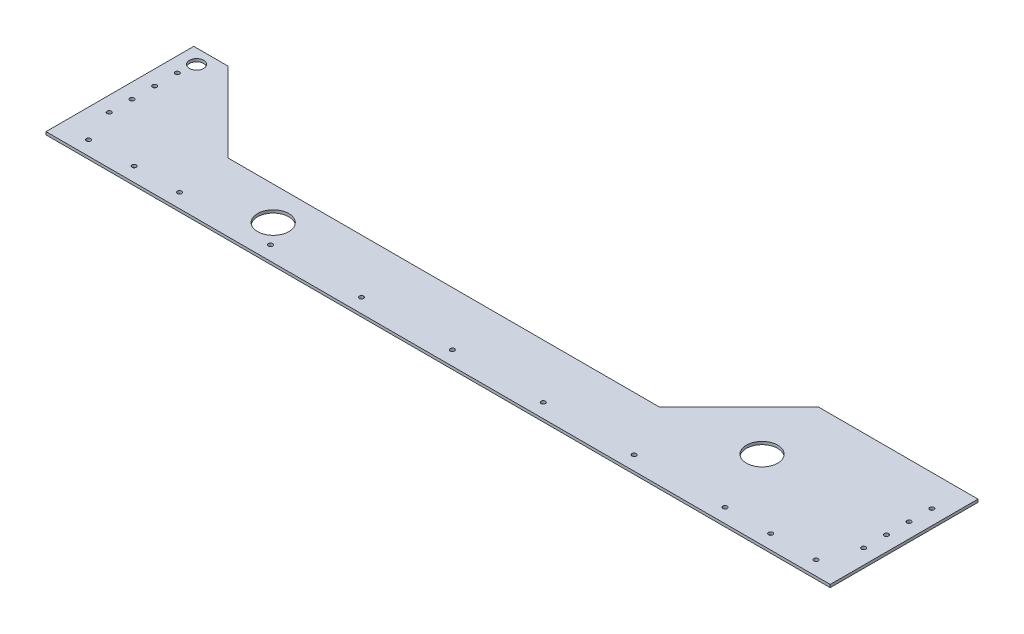
SolidWorks part; units mm, degrees
material "5052-H32"
ref_plane "Front" through (0, 0, 0) normal (0, 0, 1) x (1, 0, 0)
ref_plane "Top" through (0, 0, 0) normal (0, 1, 0) x (1, 0, 0)
ref_plane "Right" through (0, 0, 0) normal (1, 0, 0) x (0, 0, -1)
sketch "Sketch1" plane through (0, 0, 0) normal (0, 1, 0) x (1, 0, 0)
  line L0 (0, 0) -> (214.9475, 0) construction
  line L1 (214.9475, 0) -> (214.9475, 38.9255) construction
  line L2 (214.9475, 38.9255) -> (712.1677, 38.9255) construction
  line L3 (712.1677, 38.9255) -> (712.1677, 87.9475) construction
  line L4 (0, 0) -> (876.3, 0)
  line L5 (876.3, 0) -> (876.3, 165.1)
  line L6 (0, 0) -> (0, 165.1)
  line L7 (0, 165.1) -> (38.1, 165.1)
  line L8 (38.1, 165.1) -> (127, 76.2)
  line L9 (127, 76.2) -> (609.6, 76.2)
  line L10 (876.3, 165.1) -> (698.5, 165.1)
  line L11 (609.6, 76.2) -> (698.5, 165.1)
  line L12 (438.15, 0) -> (438.15, 76.2) construction
  line L13 (0, 38.1) -> (876.3, 38.1) construction
  line L14 (38.1, 165.1) -> (38.1, 38.1) construction
  line L15 (838.2, 165.1) -> (838.2, 38.1) construction
  line L16 (742.95, 15.875) -> (844.55, 15.875) construction
  line L17 (31.75, 15.875) -> (133.35, 15.875) construction
  circle A0 centre (214.9475, 38.9255) radius 17.4625
  circle A1 centre (712.1677, 87.9475) radius 17.4625
  circle A2 centre (438.15, 15.875) radius 2.4257
  circle A3 centre (539.75, 15.875) radius 2.4257
  circle A4 centre (641.35, 15.875) radius 2.4257
  circle A5 centre (742.95, 15.875) radius 2.4257
  circle A6 centre (844.55, 15.875) radius 2.4257
  circle A7 centre (31.75, 15.875) radius 2.4257
  circle A8 centre (133.35, 15.875) radius 2.4257
  circle A9 centre (234.95, 15.875) radius 2.4257
  circle A10 centre (336.55, 15.875) radius 2.4257
  circle A11 centre (16.637, 53.975) radius 2.4257
  circle A12 centre (16.637, 79.375) radius 2.4257
  circle A13 centre (16.637, 104.775) radius 2.4257
  circle A14 centre (16.637, 130.175) radius 2.4257
  circle A15 centre (859.663, 53.975) radius 2.4257
  circle A16 centre (859.663, 79.375) radius 2.4257
  circle A17 centre (859.663, 104.775) radius 2.4257
  circle A18 centre (859.663, 130.175) radius 2.4257
  circle A19 centre (82.55, 15.875) radius 2.4257
  circle A20 centre (793.75, 15.875) radius 2.4257
  circle A21 centre (19.05, 149.225) radius 7.9375
  dimension "D1" = 34.925
  dimension "D13" = 4.8514
  dimension "D23" = 15.875
  dimension "D2" = 38.9255
  dimension "D3" = 214.9475
  dimension "D4" = 497.2202
  dimension "D5" = 49.022
  dimension "D6" = 876.3
  dimension "D7" = 38.1
  dimension "D8" = 165.1
  dimension "D9" = 45
  dimension "D10" = 76.2
  dimension "D11" = 45
  dimension "D12" = 177.8
  dimension "D14" = 15.875
  dimension "D16" = 101.6
  dimension "D17" = 38.1
  dimension "D18" = 38.1
  dimension "D19" = 16.637
  dimension "D20" = 15.875
  dimension "D22" = 25.4
  dimension "D24" = 19.05
  dimension "D25" = 19.05
  dimension "D15" = 5
  dimension "D21" = 4
extrude "Boss-Extrude1" add sketch "Sketch1" along normal blind 3.175 contours L11 L9 L8 L7 L6 L4 L5 L10 A17 A15 A14 A13 A12 A11 A9 A7 A6 A5 A4 A3 A2 A1 A0 A8 A10 A16 A18
fillet "Fillet1" [suppressed] radius 50.8
fillet "Fillet2" [suppressed] radius 3.175
